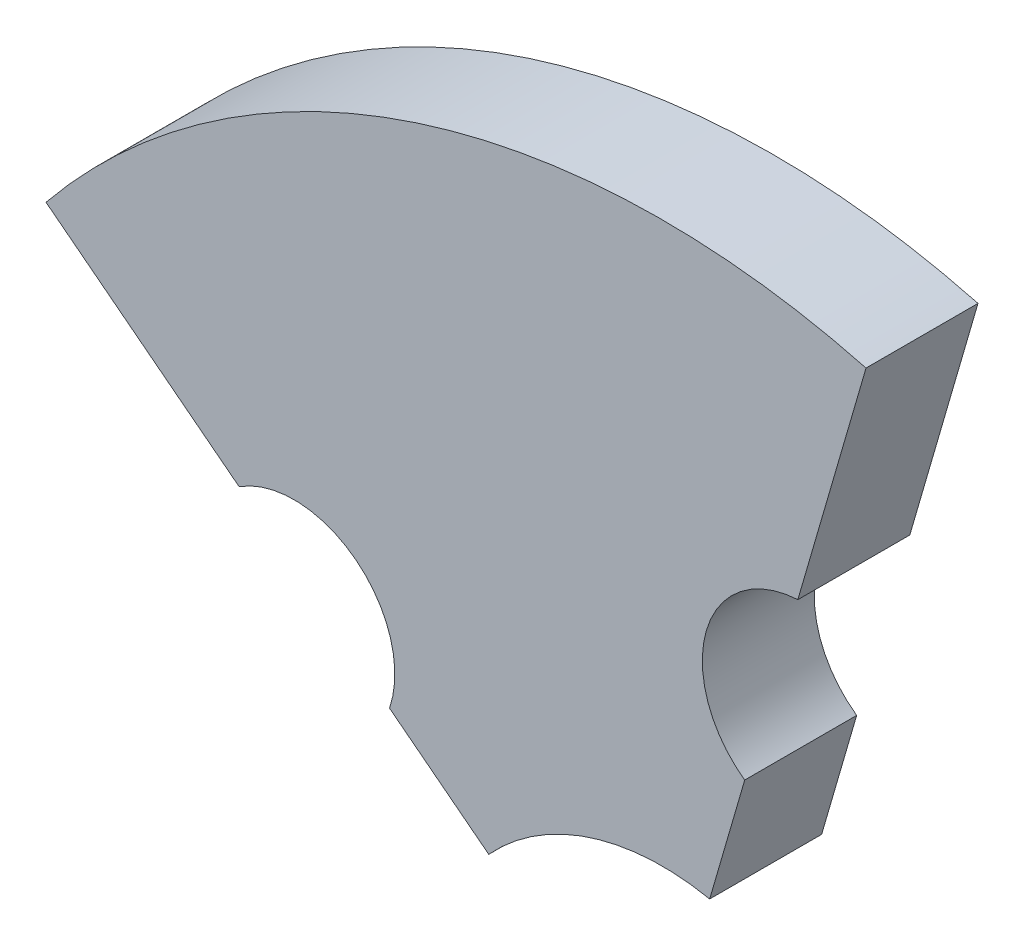
SolidWorks part; units mm, degrees
ref_plane "Front Plane" through (0, 0, 0) normal (0, 0, 1) x (1, 0, 0)
ref_plane "Top Plane" through (0, 0, 0) normal (0, 1, 0) x (1, 0, 0)
ref_plane "Right Plane" through (0, 0, 0) normal (1, 0, 0) x (0, 0, -1)
sketch "Sketch12" plane through (0, 0, 0) normal (0, 0, 1) x (1, 0, 0)
  line L0 (0, 38.1) -> (22.3946, 30.8235) construction
  line L1 (-5.8868, 18.1176) -> (15.4118, 11.1973) construction
  line L2 (4.7625, 14.6575) -> (11.1973, 34.4618) construction
  circle A0 centre (0, 0) radius 50.165
  circle A2 centre (-22.3946, 30.8235) radius 9.5631
  circle A3 centre (0, 38.1) radius 9.5631
  circle A4 centre (22.3946, 30.8235) radius 9.5631
  circle A5 centre (36.2353, 11.7735) radius 9.5631
  circle A6 centre (15.4118, 11.1973) radius 9.6393
  circle A7 centre (-5.8868, 18.1176) radius 9.6393
  circle A8 centre (0, 0) radius 8.255
  circle A9 centre (7.9799, 24.5596) radius 5.715
  point P18 (7.9799, 24.5596)
  dimension "D1" = 19.1262
  dimension "D2" = 16.51
  dimension "D3" = 100.33
  dimension "D4" = 19.2786
  dimension "D15" = 11.43
  dimension "D5" = 15.4118
  dimension "D6" = 22.3946
  dimension "D7" = 36.2353
  dimension "D8" = 5.8868
  dimension "D9" = 22.3946
  dimension "D10" = 11.1973
  dimension "D11" = 11.7735
  dimension "D12" = 18.1176
  dimension "D13" = 30.8235
  dimension "D14" = 38.1
sketch "Sketch13" plane through (0, 0, 0) normal (0, 0, 1) x (1, 0, 0)
  line L0 (11.5514, 43.5801) -> (2.6822, 13.0625)
  line L1 (-34.961, 28.4672) -> (-9.8479, 8.9912)
  circle A0 centre (0, 0) radius 13.335 construction
  circle A6 centre (0, 0) radius 8.255 construction
  circle A7 centre (0, 0) radius 8.255
  circle A8 centre (0, 0) radius 50.165 construction
  circle A9 centre (0, 0) radius 50.165
  arc A10 (2.6822, 13.0625) -> (-9.8479, 8.9912) centre (0, 0) ccw
  arc A11 (11.5514, 43.5801) -> (-34.961, 28.4672) centre (0, 0) ccw
  circle A12 centre (0, 0) radius 45.085 construction
  dimension "D3" = 2.6822
  dimension "D4" = 11.5514
  dimension "D5" = 9.8479
  dimension "D1" = 5.08
  dimension "D2" = 5.08
extrude "Boss-Extrude1" add sketch "Sketch13" against normal blind 6.35
sketch "Sketch14" plane through (0, 0, 0) normal (0, 0, 1) x (1, 0, 0)
  circle A0 centre (-22.3946, 30.8235) radius 1.27 construction
  circle A1 centre (0, 38.1) radius 1.27 construction
  circle A2 centre (-5.8868, 18.1176) radius 1.27 construction
  point P0 (-22.3946, 30.8235)
  point P1 (0, 38.1)
  point P3 (-5.8868, 18.1176)
  dimension "D1" = 2.54
  dimension "D2" = 2.54
  dimension "D3" = 2.54
sketch "Sketch15" plane through (0, 0, 0) normal (0, 0, 1) x (1, 0, 0)
  line L0 (11.5514, 43.5801) -> (2.6822, 13.0625) construction
  line L1 (7.6823, 30.2669) -> (4.6696, 19.9009)
  line L2 (0, 0) -> (-13.932, 42.8784) construction
  line L3 (-24.0055, 19.9709) -> (-15.4753, 13.3554)
  circle A0 centre (7.9799, 24.5596) radius 5.715 construction
  arc A1 (7.6823, 30.2669) -> (4.6696, 19.9009) centre (7.9799, 24.5596) ccw
  arc A2 (11.5514, 43.5801) -> (-34.961, 28.4672) centre (0, 0) ccw construction
  arc A3 (-24.0055, 19.9709) -> (-15.4753, 13.3554) centre (-20.8917, 15.1787) cw
extrude "Cut-Extrude1" cut sketch "Sketch15" against normal through all
